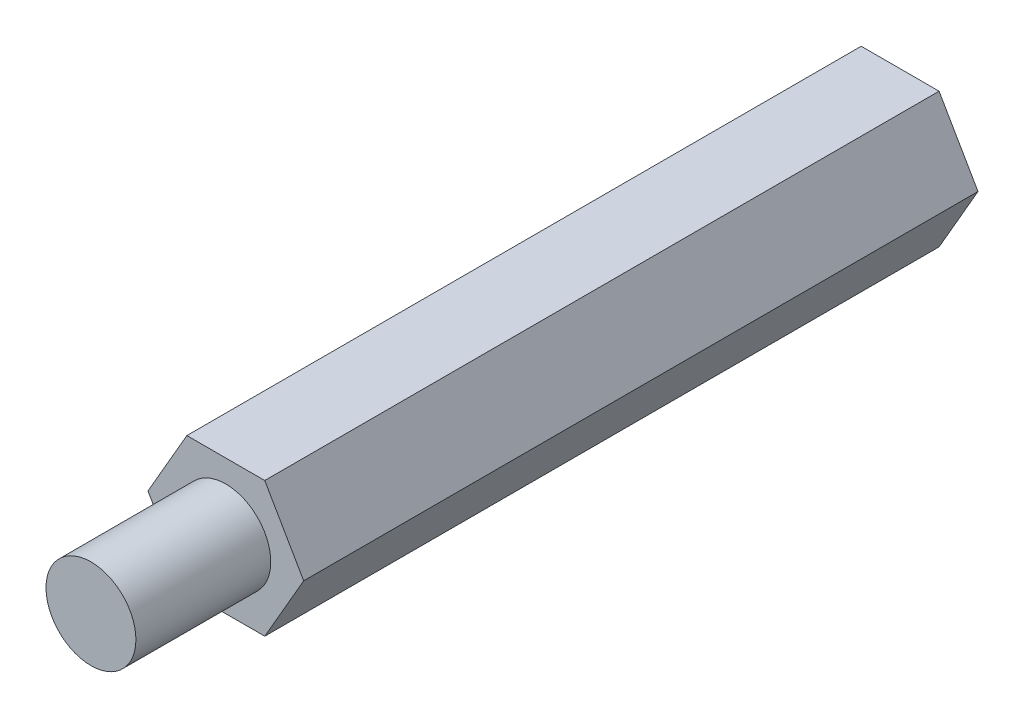
SolidWorks part; units mm, degrees
ref_plane "前视基准面" through (0, 0, 0) normal (0, 0, 1) x (1, 0, 0)
ref_plane "上视基准面" through (0, 0, 0) normal (0, 1, 0) x (1, 0, 0)
ref_plane "右视基准面" through (0, 0, 0) normal (1, 0, 0) x (0, 0, -1)
sketch "草图1" plane through (0, 0, 0) normal (0, 0, 1) x (1, 0, 0)
  line L0 (-28.6627, 0) -> (33.6774, 0) construction
  line L1 (1.7321, -3) -> (3.4641, 0)
  line L2 (3.4641, 0) -> (1.7321, 3)
  line L3 (1.7321, 3) -> (-1.7321, 3)
  line L4 (-1.7321, 3) -> (-3.4641, 0)
  line L5 (-3.4641, 0) -> (-1.7321, -3)
  line L6 (-1.7321, -3) -> (1.7321, -3)
  circle A0 centre (0, 0) radius 3 construction
  dimension "D1" = 6
extrude "拉伸1" add sketch "草图1" along normal blind 30
sketch "草图2" plane through (0, 0, 30) normal (0, 0, 1) x (1, 0, 0)
  circle A0 centre (0, 0) radius 2
  dimension "D1" = 4
extrude "拉伸2" add sketch "草图2" along normal blind 6
hole_wizard "M4 螺纹孔1" positions "3D草图2" profile "草图5" tap size "M4" standard "ISO"
sketch3d "3D草图2"
  point P0 (0, 0, 0)
  point P2 (0, 0, 0)
  point P3 (0, 0, 0)
  point P4 (0, 0, 0)
cosmetic thread "孔螺蚊线1" parameters "D1"=8, "D2"=4
sketch "草图5" plane through (0, 0, 0) normal (1, 0, 0) x (0, 1, 0)
  line L0 (0, 0) -> (0, 12.4914)
  line L1 (0, 12.4914) -> (1.65, 11.5)
  line L2 (1.65, 11.5) -> (1.65, 0)
  line L5 (1.65, 0) -> (0, 0)
  line L10 (0, 12.4914) -> (-1.65, 11.5) construction
  line L11 (0, -6.35) -> (0, 107.95) construction
  dimension "蹟恇謂郰芛眻噤" = 3.3
  dimension "蹟恇謂郰芛旮僅" = 11.5
  dimension "絳芛褒僅" = 118
cosmetic thread "孔螺蚊线2" parameters "D1"=8, "D2"=4
cosmetic thread "孔螺蚊线3" parameters "D1"=8, "D2"=4
cosmetic thread "孔螺蚊线4" parameters "D1"=8, "D2"=4
sketch "草图6" plane through (0, 0, 0) normal (0, 0, -1) x (-1, 0, 0)
  circle A0 centre (0, 0) radius 1.5
  dimension "D1" = 3
extrude "拉伸3" [suppressed] add sketch "草图6" along normal blind 10
